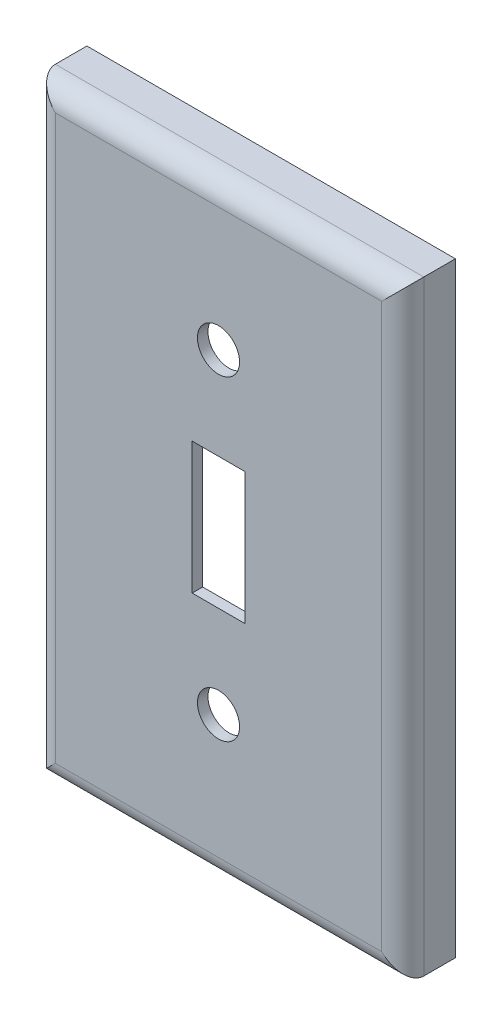
SolidWorks part; units mm, degrees
ref_plane "Alzado" through (0, 0, 0) normal (0, 0, 1) x (1, 0, 0)
ref_plane "Planta" through (0, 0, 0) normal (0, 1, 0) x (1, 0, 0)
ref_plane "Vista lateral" through (0, 0, 0) normal (1, 0, 0) x (0, 0, -1)
sketch "Croquis2" plane through (0, 0, 0) normal (0, 0, 1) x (1, 0, 0)
  line L1 (0, 0) -> (70, 0)
  line L2 (0, 0) -> (0, 115)
  line L3 (0, 115) -> (70, 115)
  line L4 (70, 0) -> (70, 115)
  dimension "D1" = 70
  dimension "D2" = 115
extrude "Saliente-Extruir1" add sketch "Croquis2" along normal blind 10
fillet "Redondeo1" radius 4 4 edges at (35, 115, 10) (70, 57.5, 10) (35, 0, 10) (0, 57.5, 10)
shell "Vaciado1" thickness 2
sketch "Croquis3" plane through (0, 0, 10) normal (0, 0, 1) x (1, 0, 0)
  line L0 (0, 115) -> (70, 115) construction
  line L1 (0, 0) -> (0, 115) construction
  line L2 (70, 0) -> (0, 0) construction
  line L3 (30, 70) -> (40, 70)
  line L4 (30, 70) -> (30, 45)
  line L5 (30, 45) -> (40, 45)
  line L6 (40, 70) -> (40, 45)
  circle A0 centre (35, 87.5) radius 4
  circle A1 centre (35, 27.5) radius 4
  dimension "D1" = 60
  dimension "D2" = 27.5
  dimension "D3" = 35
  dimension "D4" = 35
  dimension "D5" = 10
  dimension "D6" = 25
  dimension "D7" = 45
  dimension "D8" = 30
extrude "Cortar-Extruir1" cut sketch "Croquis3" against normal blind 10
